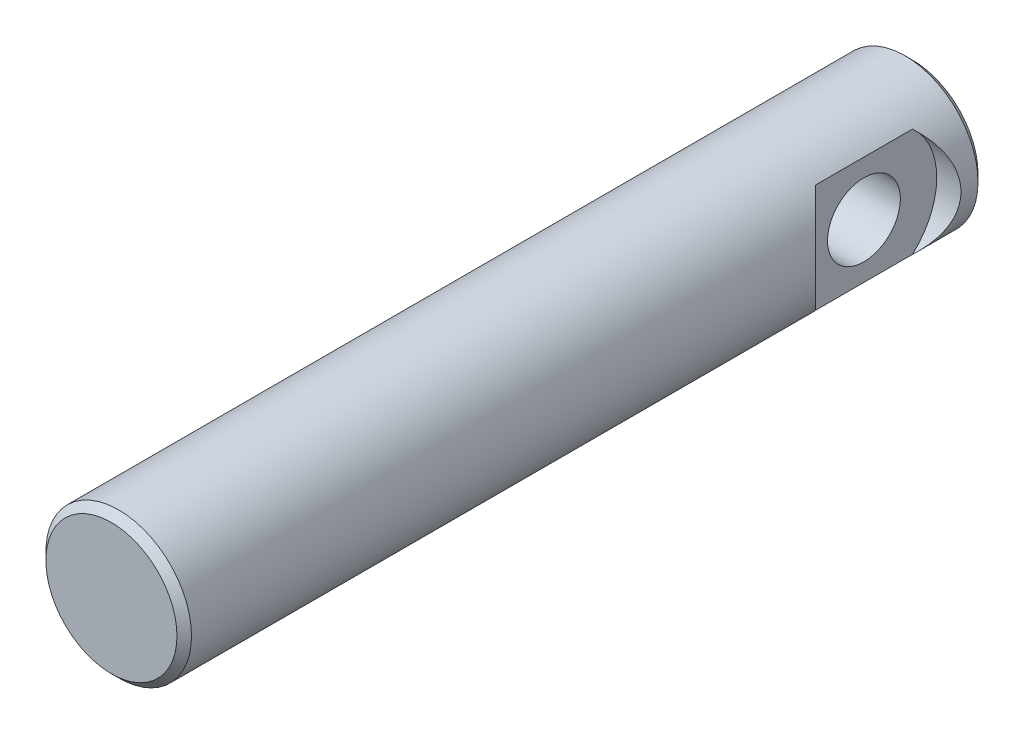
SolidWorks part; units mm, degrees
ref_plane "Front" through (0, 0, 0) normal (0, 0, 1) x (1, 0, 0)
ref_plane "Top" through (0, 0, 0) normal (0, 1, 0) x (1, 0, 0)
ref_plane "Right" through (0, 0, 0) normal (1, 0, 0) x (0, 0, -1)
sketch "Esquisse1" plane through (0, 0, 0) normal (0, 0, 1) x (1, 0, 0)
  circle A0 centre (0, 0) radius 2 construction
  circle A1 centre (0, 0) radius 3
  dimension "D1" = 6
  dimension "D2" = 4
extrude "Boss.-Extru.1" add sketch "Esquisse1" along normal blind 33
sketch "Esquisse2" plane through (0, 0, 0) normal (0, 1, 0) x (1, 0, 0)
  line L0 (-10, -2.5) -> (2, -2.5)
  line L1 (2, -2.5) -> (2, -1)
  line L2 (2, -1) -> (10, -1)
  line L3 (10, -1) -> (10, -4)
  line L4 (10, -4) -> (-10, -4)
  line L5 (-10, -4) -> (-10, -2.5)
  line L6 (10, -4) -> (13, -4) construction
  line L7 (3, 0) -> (-3, 0) construction
  point P2 (0, -4)
  point P9 (2.1598, -2.2387)
  dimension "D1" = 20
  dimension "D2" = 2
  dimension "D3" = 3
  dimension "D4" = 6
  dimension "D5" = 4
revolve "Enlèvement de matière-Révolution1" cut sketch "Esquisse2" angle 360 about L6
chamfer "Chanfrein1" distance 0.3 angle 45 2 edges at (3, 0, 0) (3, 0, 33)
